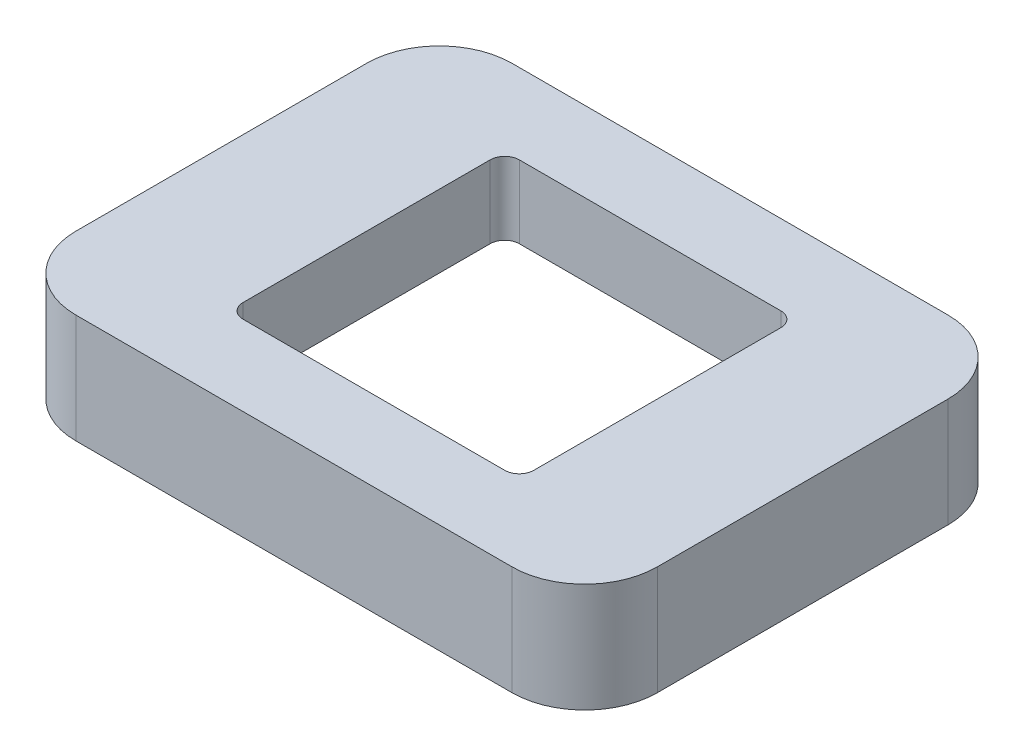
SolidWorks part; units mm, degrees
ref_plane "Plan de face" through (0, 0, 0) normal (0, 0, 1) x (1, 0, 0)
ref_plane "Plan de dessus" through (0, 0, 0) normal (0, 1, 0) x (1, 0, 0)
ref_plane "Plan de droite" through (0, 0, 0) normal (1, 0, 0) x (0, 0, -1)
sketch "Esquisse1" plane through (0, 0, 0) normal (0, 1, 0) x (1, 0, 0)
  line L1 (10, 0) -> (70, 0)
  line L2 (0, -10) -> (0, -50)
  line L3 (10, -60) -> (70, -60)
  line L4 (80, -10) -> (80, -50)
  line L13 (58, -49) -> (22, -49)
  line L14 (60, -47) -> (60, -13)
  line L15 (58, -11) -> (22, -11)
  line L16 (20, -47) -> (20, -13)
  line L17 (60, -49) -> (20, -11) construction
  line L18 (60, -11) -> (20, -49) construction
  arc A0 (0, -50) -> (10, -60) centre (10, -50) ccw
  arc A1 (80, -50) -> (70, -60) centre (70, -50) cw
  arc A2 (0, -10) -> (10, 0) centre (10, -10) cw
  arc A3 (70, 0) -> (80, -10) centre (70, -10) cw
  arc A12 (60, -13) -> (58, -11) centre (58, -13) ccw
  arc A13 (22, -11) -> (20, -13) centre (22, -13) ccw
  arc A14 (20, -47) -> (22, -49) centre (22, -47) ccw
  arc A15 (60, -47) -> (58, -49) centre (58, -47) cw
  point P9 (80, -60)
  point P12 (0, 0)
  point P15 (80, 0)
  point P16 (40, -30)
  dimension "D3" = 10
  dimension "D4" = 40
  dimension "D6" = 38
  dimension "D7" = 30
  dimension "D8" = 2
  dimension "D1" = 80
  dimension "D2" = 60
  dimension "D5" = 40
extrude "Boss.-Extru.1" add sketch "Esquisse1" along normal blind 15
sketch "Esquisse2" plane through (0, 0, 0) normal (0, -1, 0) x (1, 0, 0)
  line L0 (70, 0) -> (10, 0) construction
  line L1 (8, 57) -> (72, 57)
  line L2 (3, 52) -> (3, 8)
  line L3 (8, 3) -> (72, 3)
  line L4 (77, 52) -> (77, 8)
  line L5 (10, 60) -> (70, 60) construction
  line L6 (80, 50) -> (80, 10) construction
  line L7 (0, 10) -> (0, 50) construction
  arc A0 (3, 52) -> (8, 57) centre (8, 52) cw
  arc A1 (3, 8) -> (8, 3) centre (8, 8) ccw
  arc A2 (72, 3) -> (77, 8) centre (72, 8) ccw
  arc A3 (77, 52) -> (72, 57) centre (72, 52) ccw
  dimension "D5" = 5
  dimension "D1" = 3
  dimension "D2" = 3
  dimension "D3" = 3
  dimension "D4" = 3
extrude "Enlèv. mat.-Extru.1" cut sketch "Esquisse2" against normal blind 5
sketch "Esquisse3" plane through (0, 5, 0) normal (0, -1, 0) x (1, 0, 0)
  line L0 (70, 10) -> (70, 50) construction
  line L1 (70, 10) -> (10, 10) construction
  line L2 (10, 10) -> (10, 50) construction
  line L3 (10, 50) -> (70, 50) construction
  circle A0 centre (70, 10) radius 2.8
  circle A2 centre (70, 50) radius 2.8
  circle A3 centre (10, 10) radius 2.8
  circle A4 centre (10, 50) radius 2.8
  dimension "D1" = 5.6
  dimension "D2" = 10
  dimension "D3" = 10
  dimension "D4" = 10
  dimension "D5" = 10
  dimension "D6" = 10
extrude "Enlèv. mat.-Extru.2" cut sketch "Esquisse3" against normal blind 8.1
